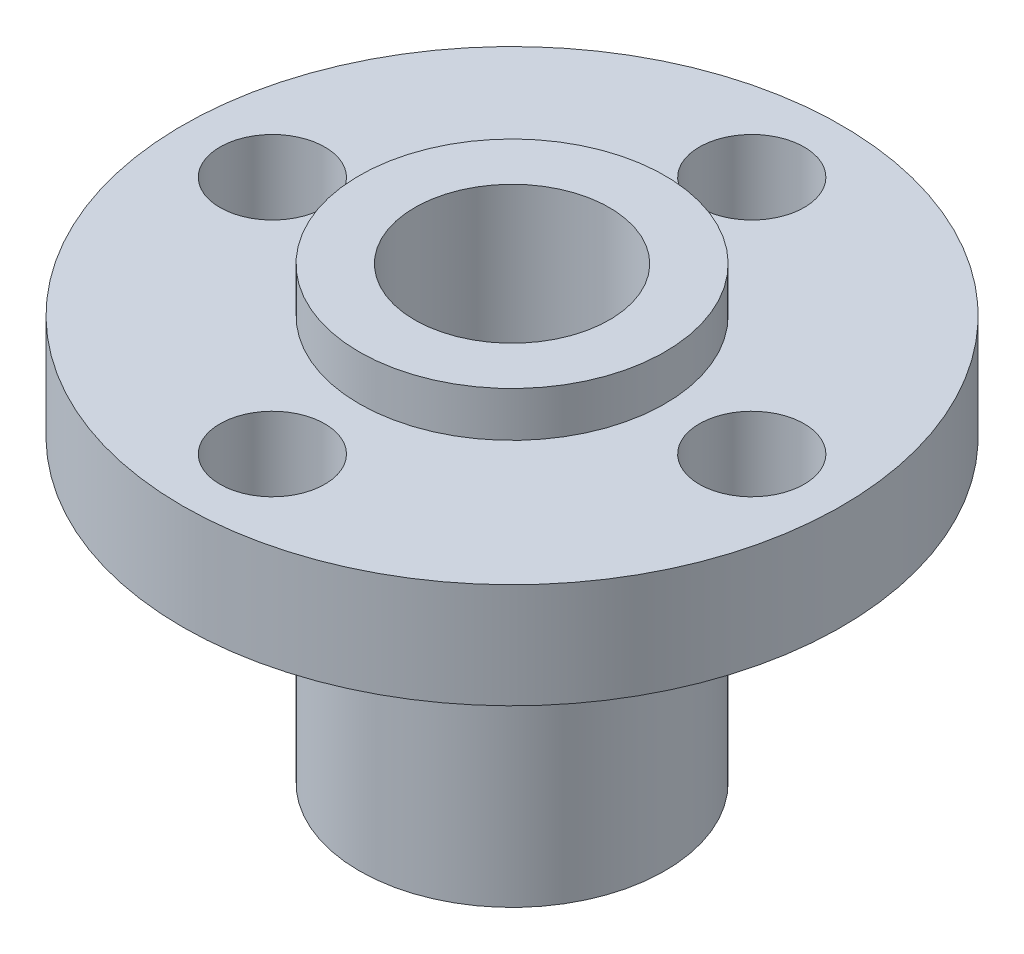
SolidWorks part; units mm, degrees
material "Brass"
ref_plane "前视基准面" through (0, 0, 0) normal (0, 0, 1) x (1, 0, 0)
ref_plane "上视基准面" through (0, 0, 0) normal (0, 1, 0) x (1, 0, 0)
ref_plane "右视基准面" through (0, 0, 0) normal (1, 0, 0) x (0, 0, -1)
sketch "Sketch1" plane through (0, 0, 0) normal (0, 1, 0) x (1, 0, 0)
  circle A0 centre (0, 0) radius 11
  dimension "D1" = 22
extrude "Boss-Extrude1" add sketch "Sketch1" along normal blind 3.5
sketch "Sketch2" plane through (0, 3.5, 0) normal (0, 1, 0) x (1, 0, 0)
  circle A0 centre (0, 0) radius 5.1
  dimension "D1" = 10.2
extrude "Boss-Extrude2" add sketch "Sketch2" along normal blind 1.5 and the other way blind 13.5
sketch "Sketch3" plane through (0, 5, 0) normal (0, 1, 0) x (1, 0, 0)
  circle A0 centre (0, 0) radius 3.25
  dimension "D1" = 6.5
extrude "Cut-Extrude1" cut sketch "Sketch3" against normal through all
cosmetic thread "Cosmetic Thread1" parameters "D2"=8
sketch "Sketch4" plane through (0, 3.5, 0) normal (0, 1, 0) x (1, 0, 0)
  line L0 (-14.9591, 0) -> (15.6931, 0) construction
  circle A0 centre (0, 0) radius 8 construction
  circle A1 centre (-8, 0) radius 1.75
  circle A2 centre (0, 8) radius 1.75
  circle A3 centre (8, 0) radius 1.75
  circle A4 centre (0, -8) radius 1.75
  point P16 (0, 0)
  dimension "D1" = 16
  dimension "D2" = 3.5
  dimension "D3" = 4
extrude "Cut-Extrude2" cut sketch "Sketch4" against normal through all
